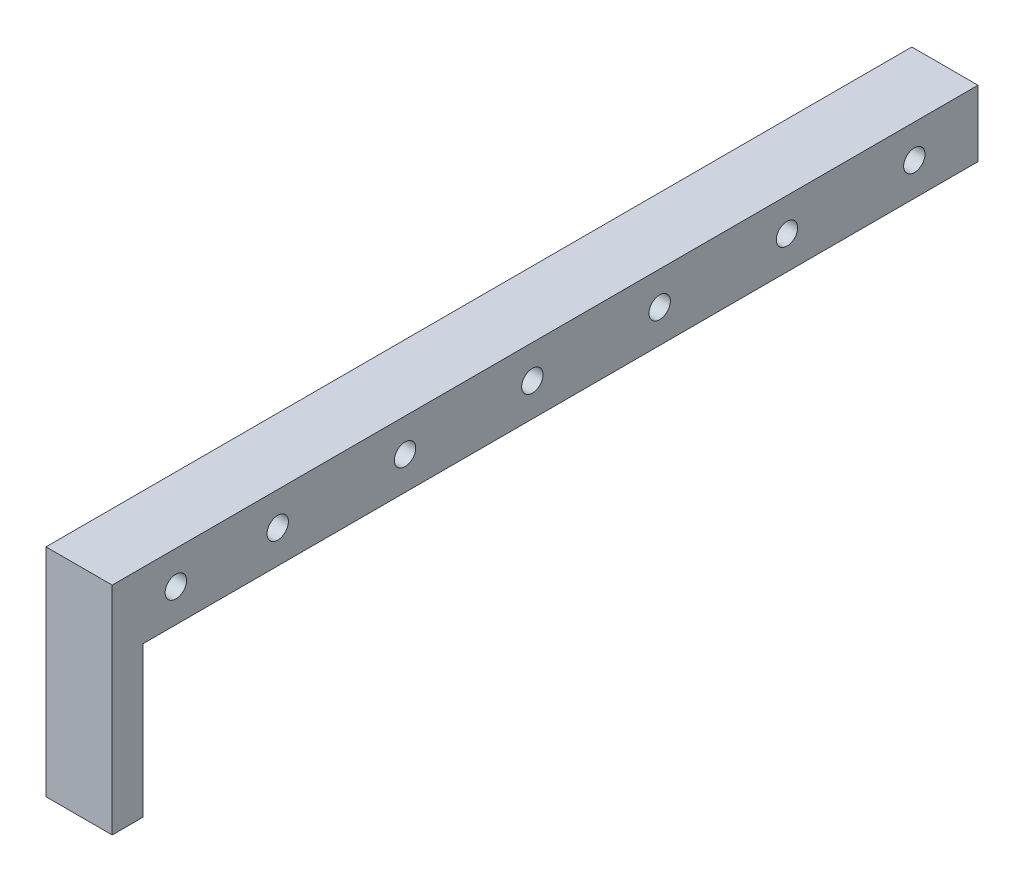
SolidWorks part; units mm, degrees
ref_plane "Front Plane" through (0, 0, 0) normal (0, 0, 1) x (1, 0, 0)
ref_plane "Top Plane" through (0, 0, 0) normal (0, 1, 0) x (1, 0, 0)
ref_plane "Right Plane" through (0, 0, 0) normal (1, 0, 0) x (0, 0, -1)
sketch "Sketch1" plane through (0, 0, 0) normal (0, 0, 1) x (1, 0, 0)
  line L0 (-6.5, -6.5) -> (6.5, -6.5)
  line L1 (6.5, -6.5) -> (6.5, 6.5)
  line L2 (6.5, 6.5) -> (-6.5, 6.5)
  line L3 (-6.5, 6.5) -> (-6.5, -6.5)
extrude "Boss-Extrude1" add sketch "Sketch1" along normal mid plane 170
ref_plane "Plane1" through (0, 0, 82) normal (0, 0, 1) x (1, 0, 0)
sketch "Sketch2" plane through (0, 0, 82) normal (0, 0, 1) x (1, 0, 0)
  line L0 (-6.5, -36) -> (6.5, -36)
  line L1 (6.5, -36) -> (6.5, -5.5)
  line L2 (6.5, -5.5) -> (-6.5, -5.5)
  line L3 (-6.5, -5.5) -> (-6.5, -36)
extrude "Boss-Extrude2" add sketch "Sketch2" along normal mid plane 6
sketch "Sketch3" plane through (0, 0, 0) normal (1, 0, 0) x (0, 0, -1)
  circle A0 centre (72.5, 0) radius 2.1
  circle A1 centre (47.5, 0) radius 2.1
  circle A2 centre (22.5, 0) radius 2.1
  circle A3 centre (-2.5, 0) radius 2.1
  circle A4 centre (-27.5, 0) radius 2.1
  circle A5 centre (-52.5, 0) radius 2.1
  circle A6 centre (-72.5, 0) radius 2.1
extrude "Cut-Extrude1" cut sketch "Sketch3" against normal mid plane 23
ref_plane "Plane2" through (-6.5, 0, 0) normal (1, 0, 0) x (0, 0, -1)
sketch "Sketch4" plane through (-6.5, 0, 0) normal (1, 0, 0) x (0, 0, -1)
  circle A0 centre (72.5, 0) radius 5.25
  circle A1 centre (47.5, 0) radius 5.25
  circle A2 centre (22.5, 0) radius 5.25
  circle A3 centre (-2.5, 0) radius 5.25
  circle A4 centre (-27.5, 0) radius 5.25
  circle A5 centre (-52.5, 0) radius 5.25
  circle A6 centre (-72.5, 0) radius 5.25
extrude "Cut-Extrude2" cut sketch "Sketch4" against normal mid plane 9
